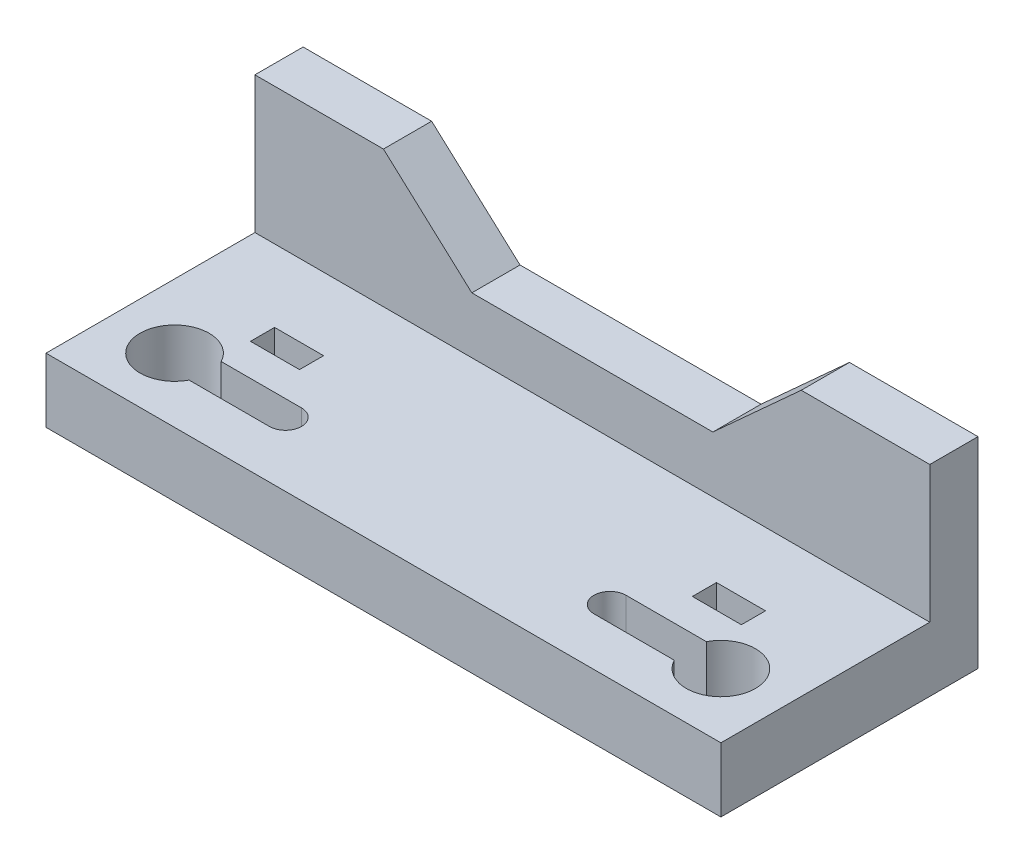
SolidWorks part; units mm, degrees
ref_plane "Front" through (0, 0, 0) normal (0, 0, 1) x (1, 0, 0)
ref_plane "Top" through (0, 0, 0) normal (0, 1, 0) x (1, 0, 0)
ref_plane "Right" through (0, 0, 0) normal (1, 0, 0) x (0, 0, -1)
sketch "Sketch2" plane through (0, 0, 0) normal (0, 1, 0) x (1, 0, 0)
  line L0 (0, 44.5764) -> (0, -12.7162) construction
  line L1 (-42, 0) -> (42, 0)
  line L2 (-42, 0) -> (-42, 32)
  line L3 (-42, 32) -> (42, 32)
  line L4 (42, 0) -> (42, 32)
  line L5 (-30.1934, 10) -> (-20.1934, 10)
  line L6 (-40.6155, 8) -> (-15.5361, 8) construction
  line L7 (-30.1934, 6) -> (-20.1934, 6)
  line L8 (30.1934, 6) -> (20.1934, 6)
  line L9 (30.1934, 10) -> (20.1934, 10)
  line L10 (-27.5, 18.5243) -> (-27.5, 12.8077) construction
  line L11 (-30.55, 17) -> (-24.45, 17)
  line L12 (-30.55, 17) -> (-30.55, 14)
  line L13 (-30.55, 14) -> (-24.45, 14)
  line L14 (-24.45, 17) -> (-24.45, 14)
  line L15 (24.45, 17) -> (24.45, 14)
  line L16 (30.55, 14) -> (24.45, 14)
  line L17 (30.55, 17) -> (30.55, 14)
  line L18 (30.55, 17) -> (24.45, 17)
  line L19 (27.5, 18.5243) -> (27.5, 12.8077) construction
  line L20 (24.45, 17) -> (24.45, 14)
  line L21 (30.55, 14) -> (24.45, 14)
  line L22 (30.55, 17) -> (30.55, 14)
  line L23 (30.55, 17) -> (24.45, 17)
  arc A0 (-20.1934, 10) -> (-20.1934, 6) centre (-20.1934, 8) cw
  arc A1 (-30.1934, 10) -> (-30.1934, 6) centre (-34, 8) ccw
  arc A2 (30.1934, 10) -> (30.1934, 6) centre (34, 8) cw
  arc A3 (20.1934, 10) -> (20.1934, 6) centre (20.1934, 8) ccw
  dimension "D3" = 4.3
  dimension "D1" = 32
  dimension "D2" = 84
  dimension "D4" = 4
  dimension "D5" = 10
  dimension "D6" = 24
  dimension "D7" = 68
  dimension "D8" = 3
  dimension "D9" = 6.1
  dimension "D10" = 6
  dimension "D11" = 55
extrude "Boss-Extrude2" add sketch "Sketch2" along normal blind 8 contours L1 L4 L3 L2 A3 L9 A2 L8 A1 L5 A0 L7 L18 L17 L16 L15 L11 L14 L13 L12
sketch "Sketch3" plane through (0, 0, -32) normal (0, 0, -1) x (-1, 0, 0)
  line L0 (-42, 8) -> (-42, 25)
  line L1 (-42, 25) -> (-26, 25)
  line L2 (-26, 25) -> (-15, 15)
  line L3 (-15, 15) -> (15, 15)
  line L4 (15, 15) -> (26, 25)
  line L5 (26, 25) -> (42, 25)
  line L6 (42, 25) -> (42, 8)
  line L7 (42, 8) -> (-42, 8)
  line L8 (0, 29.0943) -> (0, -5.1007) construction
  line L9 (42, 0) -> (-42, 0) construction
  dimension "D1" = 25
  dimension "D2" = 30
  dimension "D3" = 10
  dimension "D4" = 16
extrude "Boss-Extrude3" add sketch "Sketch3" against normal blind 6
sketch "Sketch4" plane through (0, 0, -32) normal (0, 0, -1) x (-1, 0, 0)
  line L0 (0, 24.8869) -> (0, -3.59) construction
  line L1 (42, 0) -> (-42, 0) construction
  circle A0 centre (32, 15) radius 5.5
  circle A1 centre (-32, 15) radius 5.5
  dimension "D1" = 11
  dimension "D2" = 15
  dimension "D3" = 64
extrude "Cut-Extrude1" cut sketch "Sketch4" against normal blind 1
sketch "Sketch5" plane through (0, 0, 0) normal (0, 0, 1) x (1, 0, 0)
  line L0 (0, 19.7092) -> (0, -8.0535) construction
  line L1 (8.1596, 8) -> (8.1596, 0)
  line L2 (42, 8) -> (-42, 8) construction
  line L3 (-42, 0) -> (42, 0) construction
  line L4 (8.1596, 0) -> (9.6596, 0)
  line L5 (9.6596, 0) -> (9.6596, 1)
  line L6 (9.6596, 1) -> (10.6596, 1)
  line L7 (10.6596, 1) -> (9.6596, 2)
  line L8 (9.6596, 2) -> (9.6596, 3)
  line L9 (9.6596, 3) -> (10.6596, 3)
  line L10 (10.6596, 3) -> (9.6596, 4)
  line L11 (9.6596, 4) -> (9.6596, 5)
  line L12 (9.6596, 5) -> (10.6596, 5)
  line L13 (10.6596, 5) -> (9.6596, 6)
  line L14 (9.6596, 6) -> (9.6596, 7)
  line L15 (9.6596, 7) -> (10.6596, 7)
  line L16 (10.6596, 7) -> (9.6596, 8)
  line L17 (9.6596, 8) -> (8.1596, 8)
  dimension "D1" = 1
  dimension "D2" = 1
  dimension "D3" = 1.5
  dimension "D4" = 4
